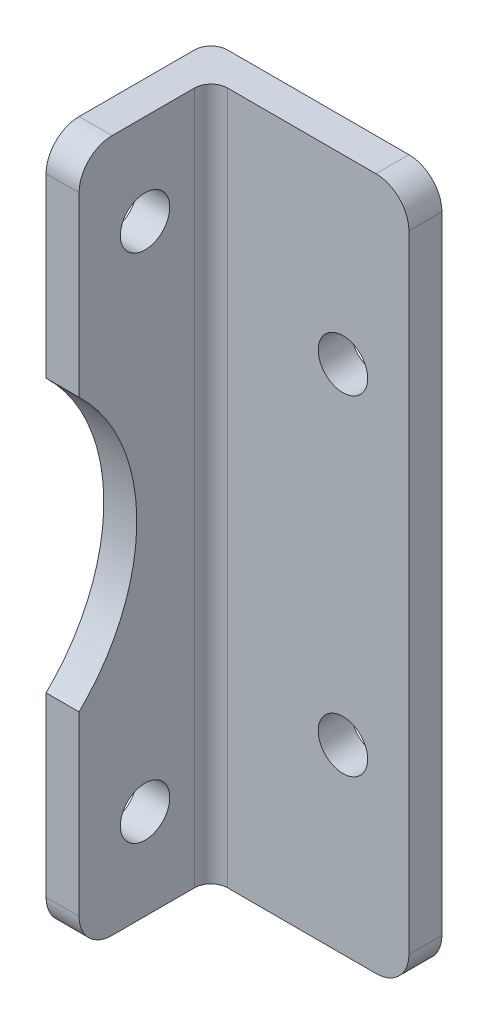
SolidWorks part; units mm, degrees
ref_plane "前视基准面" through (0, 0, 0) normal (0, 0, 1) x (1, 0, 0)
ref_plane "上视基准面" through (0, 0, 0) normal (0, 1, 0) x (1, 0, 0)
ref_plane "右视基准面" through (0, 0, 0) normal (1, 0, 0) x (0, 0, -1)
sketch "草图1" plane through (0, 0, 0) normal (0, 0, 1) x (1, 0, 0)
  line L0 (0.4905, 1.0867) -> (0.4905, -18.9133)
  line L5 (-9.5095, 12.0867) -> (4.4905, 12.0867)
  line L6 (-9.5095, 12.0867) -> (-9.5095, -29.9133)
  line L7 (-9.5095, -29.9133) -> (4.4905, -29.9133)
  line L8 (4.4905, 12.0867) -> (4.4905, -29.9133)
  circle A0 centre (0.4905, 1.0867) radius 1.5
  circle A1 centre (0.4905, -18.9133) radius 1.5
  point P8 (0.4905, -8.9133)
  point P9 (4.4905, -8.9133)
  dimension "D5" = 3
  dimension "D6" = 3
  dimension "D1" = 42
  dimension "D2" = 20
  dimension "D3" = 4
  dimension "D4" = 14
extrude "凸台-拉伸1" add sketch "草图1" along normal blind 2
sketch "草图2" plane through (-9.5095, 0, 0) normal (-1, 0, 0) x (0, 0, 1)
  line L0 (2, -29.9133) -> (0, -29.9133) construction
  line L1 (2, 12.0867) -> (10, 12.0867)
  line L2 (2, 12.0867) -> (2, -29.9133)
  line L3 (2, -29.9133) -> (10, -29.9133)
  line L4 (10, 12.0867) -> (10, -29.9133)
  line L5 (6, 6.5867) -> (6, -24.4133)
  line L6 (0, 12.0867) -> (0, -29.9133) construction
  circle A0 centre (6, 6.5867) radius 1.5
  circle A1 centre (6, -24.4133) radius 1.5
  circle A2 centre (18, -8.9133) radius 11.5
  point P11 (6, -8.9133)
  point P12 (10, -8.9133)
  dimension "D3" = 3
  dimension "D4" = 3
  dimension "D6" = 23
  dimension "D1" = 8
  dimension "D2" = 31
  dimension "D5" = 6
  dimension "D7" = 18
extrude "凸台-拉伸2" add sketch "草图2" against normal blind 2
fillet "圆角1" radius 2 4 edges at (-8.5095, 12.0867, 10) (-8.5095, -29.9133, 10) (4.4905, 12.0867, 1) (4.4905, -29.9133, 1)
fillet "圆角2" radius 1 2 edges at (-9.5095, -8.9133, 0) (-7.5095, -8.9133, 2)
